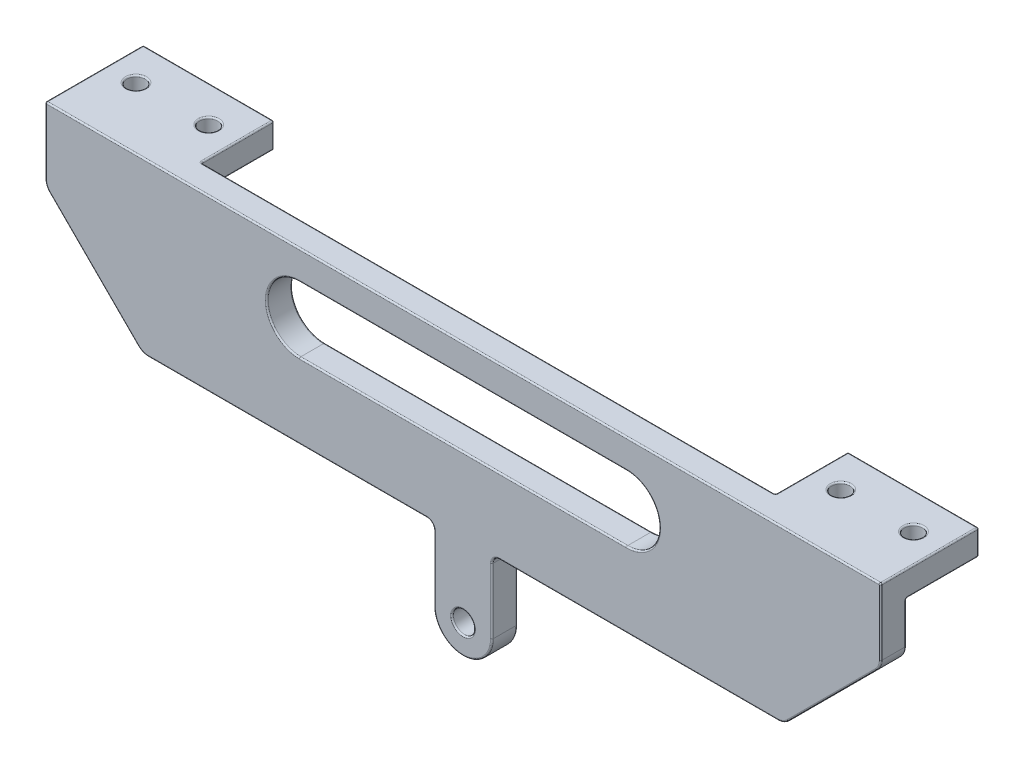
SolidWorks part; units mm, degrees
ref_plane "Front Plane" through (0, 0, 0) normal (0, 0, 1) x (1, 0, 0)
ref_plane "Top Plane" through (0, 0, 0) normal (0, 1, 0) x (1, 0, 0)
ref_plane "Right Plane" through (0, 0, 0) normal (1, 0, 0) x (0, 0, -1)
sketch "Sketch1" plane through (0, 0, 0) normal (0, 0, 1) x (1, 0, 0)
  line L0 (100, 0) -> (-100, 0) construction
  line L1 (-100, 0) -> (0, 100) construction
  line L2 (0, 100) -> (100, 0) construction
  line L3 (0, 0) -> (-50, 50) construction
  line L4 (-40, 60) -> (40, 60) construction
  line L5 (0, 100) -> (0, 60) construction
  circle A0 centre (-100, 0) radius 20
  circle A1 centre (0, 0) radius 20
  circle A2 centre (100, 0) radius 20
  point P2 (0, 0)
  dimension "D5" = 40
  dimension "D1" = 200
  dimension "D2" = 90
  dimension "D3" = 90
  dimension "D4" = 80
sketch "Sketch2" plane through (0, 0, 0) normal (0, 0, 1) x (1, 0, 0)
  line L0 (93.636, 20.5061) -> (79.4939, 6.364)
  line L1 (-56.5165, 43.4835) -> (-40, 60) construction
  line L2 (-100, 0) -> (0, 100) construction
  line L3 (-40, 60) -> (40, 60) construction
  line L4 (40, 60) -> (86.565, 13.435) construction
  line L5 (0, 100) -> (100, 0) construction
  line L6 (-49.4454, 36.4124) -> (-35.8579, 50)
  line L7 (-35.8579, 50) -> (35.8579, 50)
  line L8 (35.8579, 50) -> (79.4939, 6.364)
  line L9 (-63.5876, 50.5546) -> (-44.1421, 70)
  line L10 (-44.1421, 70) -> (44.1421, 70)
  line L11 (44.1421, 70) -> (93.636, 20.5061)
  line L12 (-63.5876, 50.5546) -> (-49.4454, 36.4124)
  line L13 (82.1491, 9.0191) -> (95.3424, -4.534)
  line L14 (90.9809, 17.8509) -> (104.534, 4.6576)
  line L15 (90.1005, 24.0416) -> (75.9584, 9.8995) construction
  line L17 (6, 70) -> (3.4532, 85.4203)
  line L18 (-6, 70) -> (-3.4532, 85.4203)
  line L19 (0, 100) -> (0, 60) construction
  circle A0 centre (100, 0) radius 3.5
  circle A1 centre (100, 0) radius 10 construction
  arc A2 (95.3424, -4.534) -> (104.534, 4.6576) centre (100, 0) ccw
  circle A3 centre (100, 0) radius 20 construction
  circle A4 centre (86.565, 20.5061) radius 1
  circle A5 centre (100, 0) radius 6.5 construction
  circle A6 centre (79.4939, 13.435) radius 1
  circle A7 centre (0, 60) radius 1.5
  circle A8 centre (0, 84.85) radius 1.5
  arc A9 (3.4532, 85.4203) -> (-3.4532, 85.4203) centre (0, 84.85) ccw
  circle A10 centre (-50, 50) radius 1.5
  circle A11 centre (0, 84.85) radius 3.5 construction
  point P32 (106.5, 0)
  point P52 (3.5, 82)
  dimension "D4" = 20
  dimension "D5" = 7
  dimension "D9" = 2
  dimension "D12" = 3
  dimension "D17" = 3
  dimension "D3" = 27.5
  dimension "D7" = 19
  dimension "D8" = 5
  dimension "D10" = 5
  dimension "D11" = 5
  dimension "D13" = 14.85
  dimension "D15" = 6
  dimension "D16" = 6
  dimension "D1" = 10
  dimension "D2" = 10
  dimension "D6" = 3
  dimension "D14" = 2
sketch "Sketch3" plane through (0, 0, 0) normal (0, 0, 1) x (1, 0, 0)
  line L0 (-86.565, 13.435) -> (-50, 50) construction
  line L1 (-100, 0) -> (0, 100) construction
  line L2 (-50, 50) -> (-13.435, 13.435) construction
  line L3 (0, 0) -> (-50, 50) construction
  line L4 (-79.4939, 6.364) -> (-50, 35.8579)
  line L5 (-50, 35.8579) -> (-20.5061, 6.364)
  line L6 (-93.636, 20.5061) -> (-50, 64.1421)
  line L7 (-50, 64.1421) -> (-6.364, 20.5061)
  line L8 (-79.4939, 6.364) -> (-50, 35.8579) construction
  line L9 (-93.636, 20.5061) -> (-50, 64.1421) construction
  line L10 (-93.636, 20.5061) -> (-79.4939, 6.364)
  line L11 (-6.364, 20.5061) -> (-20.5061, 6.364)
  line L12 (-104.534, 4.6576) -> (-90.9809, 17.8509)
  line L13 (-82.1491, 9.0191) -> (-95.3424, -4.534)
  line L14 (-17.8509, 9.0191) -> (-4.6576, -4.534)
  line L15 (-9.0191, 17.8509) -> (4.534, 4.6576)
  line L16 (-9.8995, 24.0416) -> (-24.0416, 9.8995) construction
  line L17 (-90.1005, 24.0416) -> (-75.9584, 9.8995) construction
  circle A0 centre (-100, 0) radius 3.5
  circle A1 centre (-100, 0) radius 10 construction
  circle A2 centre (0, 0) radius 3.5
  circle A3 centre (0, 0) radius 10 construction
  arc A4 (-104.534, 4.6576) -> (-95.3424, -4.534) centre (-100, 0) ccw
  arc A5 (-4.6576, -4.534) -> (4.534, 4.6576) centre (0, 0) ccw
  circle A6 centre (-100, 0) radius 20 construction
  circle A7 centre (0, 0) radius 20 construction
  circle A8 centre (-86.565, 20.5061) radius 1
  circle A9 centre (-100, 0) radius 6.5 construction
  circle A10 centre (0, 0) radius 6.5 construction
  circle A11 centre (-79.4939, 13.435) radius 1
  circle A12 centre (-20.5061, 13.435) radius 1
  circle A13 centre (-13.435, 20.5061) radius 1
  circle A14 centre (-50, 50) radius 1.5 construction
  circle A15 centre (-50, 50) radius 1.5
  point P9 (6.5, 0)
  point P43 (-93.5, 0)
  dimension "D1" = 20
  dimension "D2" = 7
  dimension "D8" = 2
  dimension "D6" = 19
  dimension "D7" = 19
  dimension "D9" = 5
  dimension "D10" = 5
  dimension "D11" = 5
  dimension "D12" = 5
  dimension "D13" = 5
  dimension "D14" = 5
  dimension "D3" = 3
  dimension "D4" = 10
  dimension "D5" = 10
sketch "Sketch4" plane through (0, 0, 0) normal (0, 0, 1) x (1, 0, 0)
  line L0 (-57.5062, 93.35) -> (57.4938, 93.35)
  line L1 (57.4938, 93.35) -> (57.4938, 83.35)
  line L2 (57.4938, 83.35) -> (44.1421, 70)
  line L3 (44.1421, 70) -> (-44.1421, 70)
  line L4 (-44.1421, 70) -> (-57.5062, 83.35)
  line L5 (-57.5062, 83.35) -> (-57.5062, 93.35)
  line L6 (4, 60) -> (4, 70)
  line L7 (-4, 60) -> (-4, 70)
  line L8 (-22.5, 84.85) -> (22.5, 84.85) construction
  line L9 (-22.5, 89.35) -> (22.5, 89.35)
  line L10 (-22.5, 80.35) -> (22.5, 80.35)
  circle A0 centre (0, 60) radius 1.5 construction
  circle A1 centre (0, 60) radius 1.5
  arc A2 (-4, 60) -> (4, 60) centre (0, 60) ccw
  arc A3 (-22.5, 89.35) -> (-22.5, 80.35) centre (-22.5, 84.85) ccw
  circle A4 centre (0, 60) radius 4 construction
  arc A5 (22.5, 80.35) -> (22.5, 89.35) centre (22.5, 84.85) ccw
  point P20 (4, 60)
  point P23 (0, 84.85)
  dimension "D5" = 9
  dimension "D1" = 115
  dimension "D2" = 10
  dimension "D4" = 45
  dimension "D6" = 4
  dimension "D3" = 2.5
sketch "Sketch5" plane through (0, 0, 0) normal (0, 0, 1) x (1, 0, 0)
  line L0 (4, 60) -> (4, 70) construction
  line L1 (-4, 60) -> (-4, 70) construction
  line L2 (22.5, 89.35) -> (-22.5, 89.35)
  line L3 (-22.5, 80.35) -> (22.5, 80.35)
  line L4 (22.5, 89.35) -> (-22.5, 89.35)
  line L5 (-22.5, 80.35) -> (22.5, 80.35)
  line L6 (57.4938, 93.35) -> (-57.5062, 93.35)
  line L7 (57.4938, 83.35) -> (57.4938, 93.35)
  line L8 (44.1421, 70) -> (57.4938, 83.35)
  line L9 (-44.1421, 70) -> (44.1421, 70)
  line L10 (-57.5062, 83.35) -> (-44.1421, 70)
  line L11 (-57.5062, 93.35) -> (-57.5062, 83.35)
  line L12 (57.4938, 93.35) -> (-57.5062, 93.35)
  line L13 (57.4938, 83.35) -> (57.4938, 93.35)
  line L14 (44.1421, 70) -> (57.4938, 83.35)
  line L15 (-44.1421, 70) -> (-4, 70)
  line L16 (-57.5062, 83.35) -> (-44.1421, 70)
  line L17 (-57.5062, 93.35) -> (-57.5062, 83.35)
  line L18 (4, 60) -> (4, 70)
  line L19 (-4, 60) -> (-4, 70)
  line L20 (4, 70) -> (44.1421, 70)
  arc A0 (-4, 60) -> (4, 60) centre (0, 60) ccw construction
  circle A1 centre (0, 60) radius 1.5
  circle A2 centre (0, 60) radius 1.5
  arc A3 (-4, 60) -> (4, 60) centre (0, 60) ccw
  arc A4 (22.5, 80.35) -> (22.5, 89.35) centre (22.5, 84.85) ccw
  arc A5 (-22.5, 89.35) -> (-22.5, 80.35) centre (-22.5, 84.85) ccw
  arc A6 (22.5, 80.35) -> (22.5, 89.35) centre (22.5, 84.85) ccw
  arc A7 (-22.5, 89.35) -> (-22.5, 80.35) centre (-22.5, 84.85) ccw
  dimension "D1" = 0
  dimension "D2" = 0
  dimension "D3" = 0
extrude "Boss-Extrude1" add sketch "Sketch5" along normal blind 3.5
sketch "Sketch6" plane through (0, 93.35, 0) normal (0, 1, 0) x (1, 0, 0)
  line L0 (-57.5062, 0) -> (-39.5062, 0)
  line L1 (57.4938, 0) -> (-57.5062, 0) construction
  line L2 (-39.5062, 0) -> (-39.5062, 10)
  line L3 (-39.5062, 10) -> (-57.5062, 10)
  line L4 (-57.5062, 10) -> (-57.5062, 0)
  line L5 (-57.5062, 5) -> (-39.5062, 5) construction
  line L6 (-48.5062, 5) -> (-48.5062, 10) construction
  line L7 (39.4938, 5) -> (57.4938, 5) construction
  line L8 (57.4938, 0) -> (39.4938, 0)
  line L9 (57.4938, 0) -> (57.4938, 10)
  line L14 (57.4938, 10) -> (39.4938, 10)
  line L15 (39.4938, 0) -> (39.4938, 10)
  line L16 (48.4938, 10) -> (48.4938, 5) construction
  circle A0 centre (-53.5062, 5) radius 1.25
  circle A1 centre (-43.5062, 5) radius 1.25
  circle A4 centre (43.4938, 5) radius 1.25
  circle A5 centre (53.4938, 5) radius 1.25
  dimension "D4" = 2.5
  dimension "D7" = 2.5
  dimension "D1" = 18
  dimension "D2" = 10
  dimension "D3" = 10
  dimension "D5" = 18
  dimension "D6" = 10
  dimension "D8" = 10
extrude "Boss-Extrude2" add sketch "Sketch6" against normal blind 3.5
fillet "Fillet1" radius 2 4 edges at (57.4938, 83.35, 1.75) (44.1421, 70, 1.75) (-44.1421, 70, 1.75) (-57.5062, 83.35, 1.75)
fillet "Fillet2" radius 1 2 edges at (4, 70, 1.75) (-4, 70, 1.75)
fillet "Fillet5" radius 0.2 70 edges at (53.4938, 93.35, -3.75) (53.4938, 89.85, -3.75) (43.4938, 93.35, -3.75) (43.4938, 89.85, -3.75) (48.4938, 93.35, -10) (48.4938, 89.85, -10) (39.4938, 93.35, -5) (39.4938, 89.85, -5) (57.4938, 89.85, -5) (48.4938, 89.85, 0) (57.4938, 91.6, -10) (39.4938, 91.6, -10) (39.4938, 91.6, 0) (-43.5062, 93.35, -3.75) (-43.5062, 89.85, -3.75) (-53.5062, 93.35, -3.75) (-53.5062, 89.85, -3.75) (-39.5062, 93.35, -5) (-39.5062, 89.85, -5) (-48.5062, 93.35, -10) (-48.5062, 89.85, -10) (-57.5062, 89.85, -5) (-48.5062, 89.85, 0) (-39.5062, 91.6, 0) (-39.5062, 91.6, -10) (-57.5062, 91.6, -10) (0, 80.35, 0) (27, 84.85, 0) (0, 89.35, 0) (-27, 84.85, 3.5) (0, 80.35, 3.5) (27, 84.85, 3.5) (0, 89.35, 3.5) (1.5, 60, 0) (1.5, 60, 3.5) (-57.5062, 87.0145, 0) (-50.8237, 76.6746, 0) (-24.1572, 70, 0) (-4, 64.5, 0) (0, 56, 0) (4, 64.5, 0) (24.1569, 70, 0) (50.8179, 76.6749, 0) (57.4938, 87.0143, 0) (-0.0062, 93.35, 0) (-57.5062, 88.7645, 3.5) (-50.8237, 76.6746, 3.5) (-24.1572, 70, 3.5) (-4, 64.5, 3.5) (0, 56, 3.5) (4, 64.5, 3.5) (24.1569, 70, 3.5) (50.8179, 76.6749, 3.5) (57.4938, 88.7643, 3.5) (-0.0062, 93.35, 3.5) (-57.5062, 93.35, -3.25) (57.4938, 93.35, -3.25) (-57.3537, 83.4132, 0) (-44.0792, 70.152, 0) (44.0791, 70.1522, 0) (57.3416, 83.4131, 0) (-57.3537, 83.4132, 3.5) (-44.0792, 70.152, 3.5) (44.0791, 70.1522, 3.5) (57.3416, 83.4131, 3.5) (4.2929, 69.7071, 0) (4.2929, 69.7071, 3.5) (-4.2929, 69.7071, 0) (-4.2929, 69.7071, 3.5) (-27, 84.85, 0)
